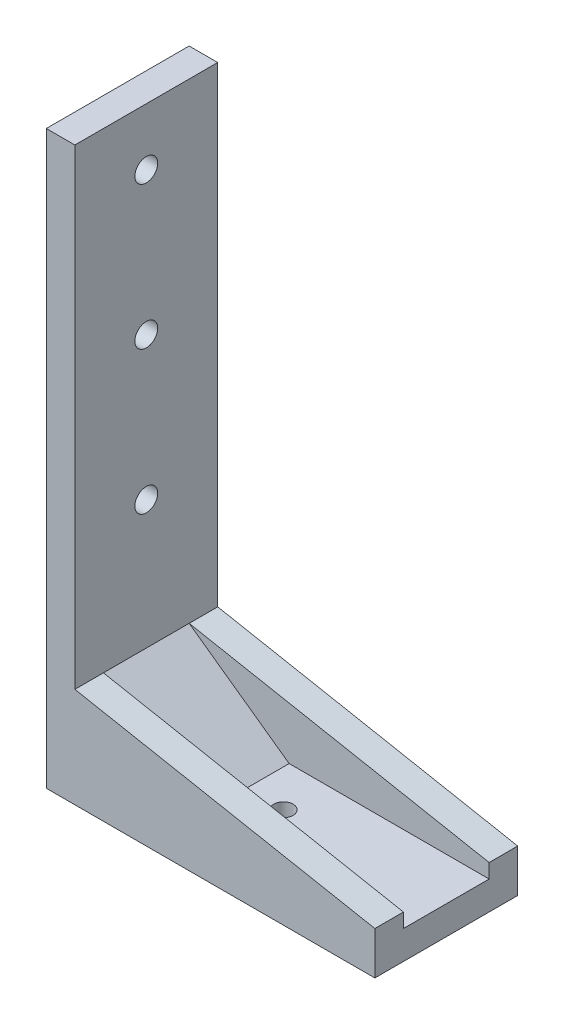
SolidWorks part; units mm, degrees
ref_plane "Front Plane" through (0, 0, 0) normal (0, 0, 1) x (1, 0, 0)
ref_plane "Top Plane" through (0, 0, 0) normal (0, 1, 0) x (1, 0, 0)
ref_plane "Right Plane" through (0, 0, 0) normal (1, 0, 0) x (0, 0, -1)
sketch "Sketch1" plane through (0, 0, 0) normal (0, 0, 1) x (1, 0, 0)
  line L0 (0, 0) -> (0, 200)
  line L1 (0, 0) -> (115, 0)
  line L2 (115, 0) -> (115, 10)
  line L3 (115, 10) -> (10, 10)
  line L4 (10, 10) -> (10, 200)
  line L5 (10, 200) -> (0, 200)
  dimension "D1" = 115
  dimension "D2" = 10
  dimension "D3" = 105
  dimension "D4" = 200
extrude "Boss-Extrude1" add sketch "Sketch1" along normal mid plane 50
sketch "Sketch3" plane through (10, 0, 0) normal (1, 0, 0) x (0, 0, -1)
  line L0 (0, 0) -> (0, 200) construction
  line L1 (-25, 200) -> (25, 200) construction
  circle A0 centre (0, 180) radius 4
  circle A1 centre (0, 130) radius 4
  circle A5 centre (0, 80) radius 4
  dimension "D1" = 8
  dimension "D3" = 8
  dimension "D6" = 50
  dimension "D5" = 8
  dimension "D2" = 20
  dimension "D4" = 50
extrude "Cut-Extrude2" cut sketch "Sketch3" against normal through all
sketch "Sketch4" plane through (0, 0, 0) normal (0, -1, 0) x (1, 0, 0)
  circle A0 centre (58, 0) radius 3.4 construction
  circle A1 centre (58, 0) radius 3.4
extrude "Cut-Extrude3" cut sketch "Sketch4" against normal up to next
sketch "Sketch5" plane through (0, 0, -25) normal (0, 0, -1) x (-1, 0, 0)
  line L0 (-45, 10) -> (-10, 10)
  line L1 (-115, 10) -> (-10, 10) construction
  line L2 (-10, 10) -> (-10, 35)
  line L3 (-10, 10) -> (-10, 200) construction
  line L4 (-10, 35) -> (-45, 10)
  dimension "D1" = 35
  dimension "D2" = 25
extrude "Boss-Extrude2" add sketch "Sketch5" against normal up to surface (50 mm away) up to face at (41.6667, 70, 25)
ref_plane "Plane1" through (0, 0, 0) normal (0, 0, -1) x (-1, 0, 0)
sketch "Sketch6" plane through (0, 0, -25) normal (0, 0, -1) x (-1, 0, 0)
  line L1 (-115, 10) -> (-10, 10)
  line L2 (-10, 10) -> (-10, 35)
  line L3 (-115, 10) -> (-115, 15)
  line L4 (-10, 35) -> (-115, 15)
  dimension "D1" = 5
extrude "Boss-Extrude3" add sketch "Sketch6" against normal blind 10
mirror "Mirror2" about plane through (0, 0, 0) normal (0, 0, -1) of "Boss-Extrude3"
